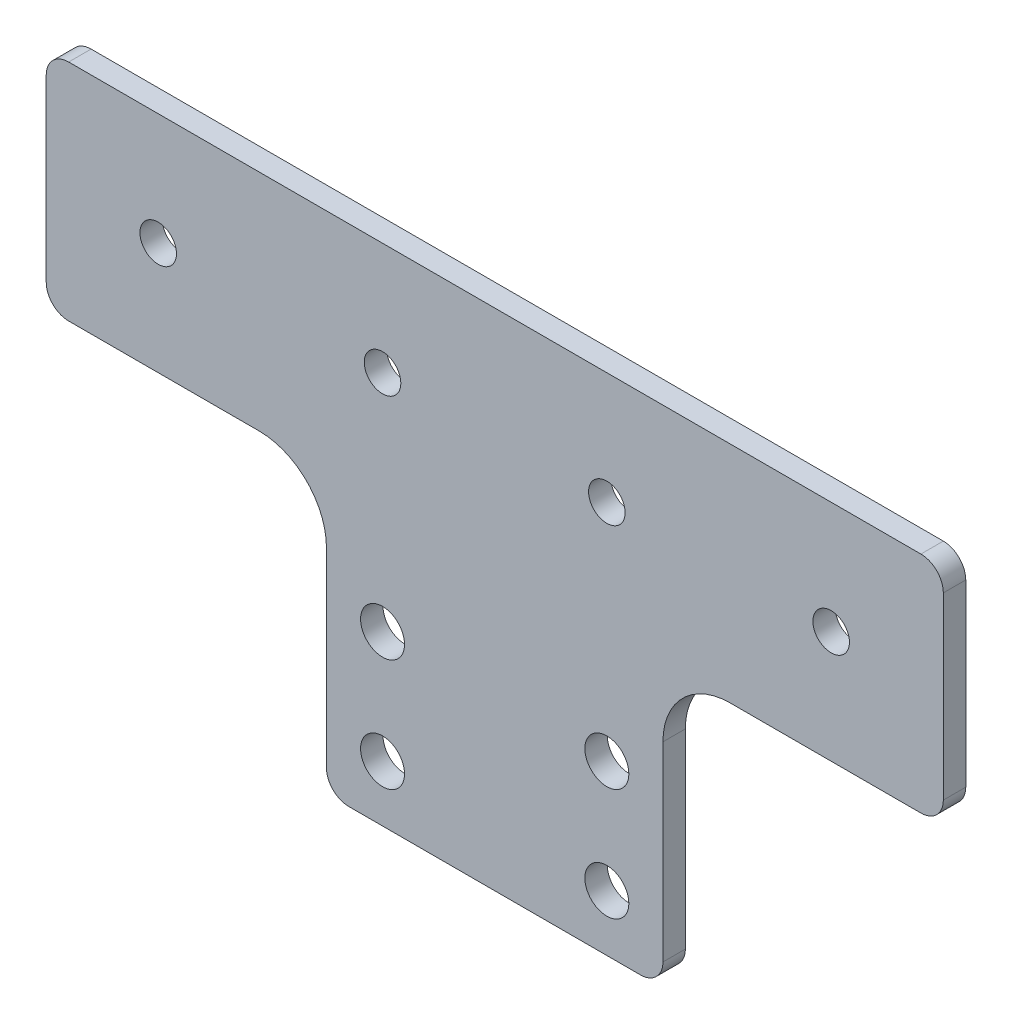
SolidWorks part; units mm, degrees
ref_plane "Front Plane" through (0, 0, 0) normal (0, 0, 1) x (1, 0, 0)
ref_plane "Top Plane" through (0, 0, 0) normal (0, 1, 0) x (1, 0, 0)
ref_plane "Right Plane" through (0, 0, 0) normal (1, 0, 0) x (0, 0, -1)
sketch "Sketch1" plane through (0, 0, 0) normal (0, 0, 1) x (1, 0, 0)
  line L0 (-35.5395, 50.8) -> (60.96, 50.8)
  line L1 (-38.0795, 48.26) -> (-38.0795, 27.94)
  line L2 (-35.5395, 25.4) -> (-13.97, 25.4)
  line L3 (63.5, 48.26) -> (63.5, 27.94)
  line L4 (39.37, 25.4) -> (60.96, 25.4)
  line L5 (-6.35, 17.78) -> (-6.35, -3.81)
  line L6 (-3.81, -6.35) -> (29.21, -6.35)
  line L7 (31.75, 17.78) -> (31.75, -3.81)
  circle A0 centre (-25.4, 38.1) radius 2.0701
  circle A1 centre (0, 38.1) radius 2.0701
  circle A2 centre (25.4, 38.1) radius 2.0701
  circle A3 centre (50.8, 38.1) radius 2.0701
  circle A4 centre (0, 12.7) radius 2.4892
  circle A5 centre (0, 0) radius 2.4892
  circle A6 centre (25.4, 12.7) radius 2.4892
  circle A7 centre (25.4, 0) radius 2.4892
  arc A8 (29.21, -6.35) -> (31.75, -3.81) centre (29.21, -3.81) ccw
  arc A9 (-6.35, -3.81) -> (-3.81, -6.35) centre (-3.81, -3.81) ccw
  arc A10 (60.96, 25.4) -> (63.5, 27.94) centre (60.96, 27.94) ccw
  arc A11 (60.96, 50.8) -> (63.5, 48.26) centre (60.96, 48.26) cw
  arc A12 (-35.5395, 50.8) -> (-38.0795, 48.26) centre (-35.5395, 48.26) ccw
  arc A13 (-38.0795, 27.94) -> (-35.5395, 25.4) centre (-35.5395, 27.94) ccw
  arc A14 (39.37, 25.4) -> (31.75, 17.78) centre (39.37, 17.78) ccw
  arc A15 (-13.97, 25.4) -> (-6.35, 17.78) centre (-13.97, 17.78) cw
  point P40 (0, 0)
  point P41 (0, 0)
  point P42 (0, 0)
  point P43 (0, 0)
  dimension "D1" = 4.1402
  dimension "D2" = 4.9784
  dimension "D8" = 2.54
  dimension "D9" = 7.62
  dimension "D14" = 38.1
  dimension "D20" = 31.75
  dimension "D3" = 12.6795
  dimension "D4" = 12.7
  dimension "D5" = 6.35
  dimension "D6" = 6.35
  dimension "D7" = 6.35
  dimension "D10" = 25.4
  dimension "D11" = 25.4
  dimension "D12" = 25.4
  dimension "D13" = 12.7
  dimension "D15" = 12.7
  dimension "D16" = 38.1
  dimension "D17" = 12.7
  dimension "D18" = 0
  dimension "D19" = 0
extrude "Boss-Extrude1" add sketch "Sketch1" along normal blind 2.54
